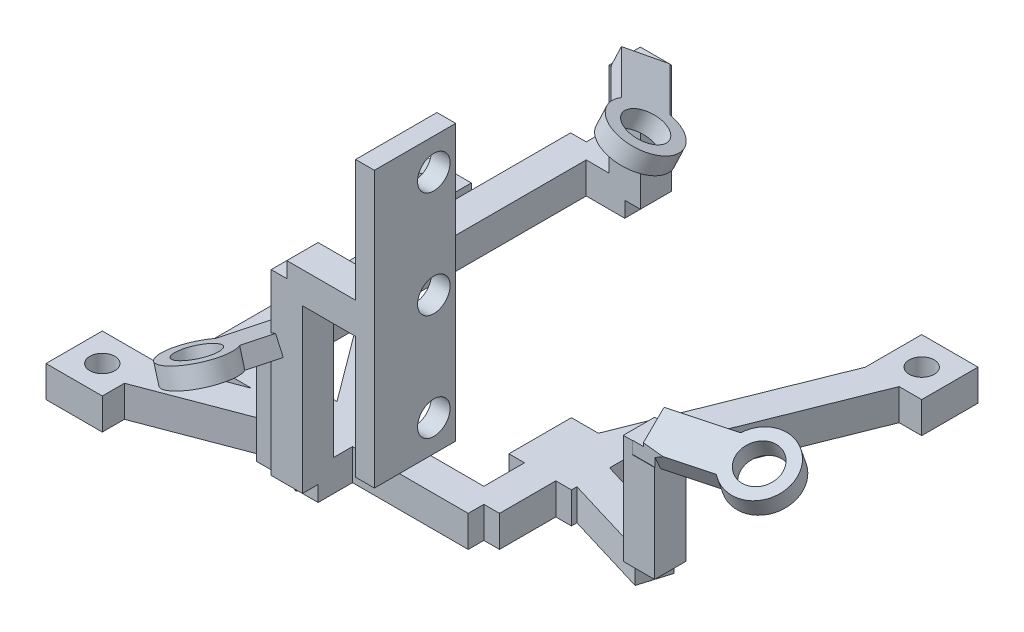
SolidWorks part; units mm, degrees
other "Cable Fairlead Support Frame"
ref_plane "Front Plane" through (0, 0, 0) normal (0, 0, 1) x (1, 0, 0)
ref_plane "Top Plane" through (0, 0, 0) normal (0, 1, 0) x (1, 0, 0)
ref_plane "Right Plane" through (0, 0, 0) normal (1, 0, 0) x (0, 0, -1)
sketch3d "Cable Fairlead Support Frame Feature profile datum points"
  point P0 (-55.2917, -60, -5)
  point P1 (-45.2917, -60, -5)
  point P2 (-55.2917, -50, -5)
ref_plane "Cable Fairlead Support Frame Feature profile plane" through (0, 0, -5) normal (0, 0, 1) x (1, 0, 0)
sketch "Cable Fairlead Support Frame Feature profile" plane through (0, 0, -5) normal (0, 0, 1) x (1, 0, 0)
  line L0 (-55.2917, -60) -> (-45.2917, -60)
  line L1 (-45.2917, -60) -> (-45.2917, -55)
  line L2 (-45.2917, -55) -> (-55.2917, -55)
  line L3 (-55.2917, -55) -> (-55.2917, -60)
extrude "Cable Fairlead Support Frame Feature" add sketch "Cable Fairlead Support Frame Feature profile" along normal blind 10 separate body
sketch3d "Frame Upper Trunk Sketch datum points"
  point P0 (-50.2917, -57.5, 0)
  point P1 (-40.2917, -57.5, 0)
  point P2 (-50.2917, -47.5, 0)
ref_plane "Frame Upper Trunk Sketch plane" through (0, 0, 0) normal (0, 0, 1) x (1, 0, 0)
sketch "Frame Upper Trunk Sketch" plane through (0, 0, 0) normal (0, 0, 1) x (1, 0, 0)
  line L0 (-52.7917, -60) -> (-47.7917, -60)
  line L1 (-47.7917, -60) -> (-47.7917, -55)
  line L2 (-47.7917, -55) -> (-52.7917, -55)
  line L3 (-52.7917, -55) -> (-52.7917, -60)
extrude "Frame Upper Trunk Feature" add sketch "Frame Upper Trunk Sketch" along normal blind 14
sketch3d "Frame Left Trunk Sketch datum points"
  point P0 (-50.2917, -57.5, 14)
  point P1 (-50.2917, -57.5, 24)
  point P2 (-50.2917, -47.5, 14)
ref_plane "Frame Left Trunk Sketch plane" through (-50.2917, 0, 0) normal (-1, 0, 0) x (0, 0, 1)
sketch "Frame Left Trunk Sketch" plane through (-50.2917, 0, 0) normal (-1, 0, 0) x (0, 0, 1)
  line L0 (11.5, -60) -> (16.5, -60)
  line L1 (16.5, -60) -> (16.5, -55)
  line L2 (16.5, -55) -> (11.5, -55)
  line L3 (11.5, -55) -> (11.5, -60)
extrude "Frame Left Trunk Feature" add sketch "Frame Left Trunk Sketch" along normal blind 21
sketch3d "Fixed Frame Mounting Web 1 Sketch datum points"
  point P0 (-71.2917, -57.5, 14)
  point P1 (-79.3163, -57.5, 19.967)
  point P2 (-71.2917, -47.5, 14)
ref_plane "Fixed Frame Mounting Web 1 Sketch plane" through (-18.6801, 0, -25.1214) normal (-0.5967, 0, -0.8025) x (-0.8025, 0, 0.5967)
sketch "Fixed Frame Mounting Web 1 Sketch" plane through (-18.6801, 0, -25.1214) normal (-0.5967, 0, -0.8025) x (-0.8025, 0, 0.5967)
  line L0 (63.0627, -60) -> (68.0627, -60)
  line L1 (68.0627, -60) -> (68.0627, -55)
  line L2 (68.0627, -55) -> (63.0627, -55)
  line L3 (63.0627, -55) -> (63.0627, -60)
extrude "Fixed Frame Mounting Web 1 Feature" add sketch "Fixed Frame Mounting Web 1 Sketch" along normal blind 48.6004
sketch3d "Prismatic M4 Mounting Pad 1 profile datum points"
  point P0 (-104.7917, -60, -29.5)
  point P1 (-94.7917, -60, -29.5)
  point P2 (-104.7917, -50, -29.5)
ref_plane "Prismatic M4 Mounting Pad 1 profile plane" through (0, 0, -29.5) normal (0, 0, 1) x (1, 0, 0)
sketch "Prismatic M4 Mounting Pad 1 profile" plane through (0, 0, -29.5) normal (0, 0, 1) x (1, 0, 0)
  line L0 (-104.7917, -60) -> (-95.7917, -60)
  line L1 (-95.7917, -60) -> (-95.7917, -55)
  line L2 (-95.7917, -55) -> (-104.7917, -55)
  line L3 (-104.7917, -55) -> (-104.7917, -60)
extrude "Prismatic M4 Mounting Pad 1" add sketch "Prismatic M4 Mounting Pad 1 profile" along normal blind 9
sketch3d "Nominal M4 Mounting Thread 1 profile datum points"
  point P0 (-100.2917, -51, -25)
  point P1 (-90.2917, -51, -25)
  point P2 (-100.2917, -51, -15)
ref_plane "Nominal M4 Mounting Thread 1 profile plane" through (0, -51, 0) normal (0, -1, 0) x (-1, 0, 0)
sketch "Nominal M4 Mounting Thread 1 profile" plane through (0, -51, 0) normal (0, -1, 0) x (-1, 0, 0)
  circle A0 centre (100.2917, 25) radius 2
extrude "Nominal M4 Mounting Thread 1" cut sketch "Nominal M4 Mounting Thread 1 profile" along normal blind 9.1
sketch3d "Fixed Frame Mounting Web 2 Sketch datum points"
  point P0 (-71.2917, -57.5, 14)
  point P1 (-67.7451, -57.5, 23.35)
  point P2 (-71.2917, -47.5, 14)
ref_plane "Fixed Frame Mounting Web 2 Sketch plane" through (-66.967, 0, 25.4013) normal (-0.935, 0, 0.3547) x (0.3547, 0, 0.935)
sketch "Fixed Frame Mounting Web 2 Sketch" plane through (-66.967, 0, 25.4013) normal (-0.935, 0, 0.3547) x (0.3547, 0, 0.935)
  line L0 (-14.6939, -60) -> (-9.6939, -60)
  line L1 (-9.6939, -60) -> (-9.6939, -55)
  line L2 (-9.6939, -55) -> (-14.6939, -55)
  line L3 (-14.6939, -55) -> (-14.6939, -60)
extrude "Fixed Frame Mounting Web 2 Feature" add sketch "Fixed Frame Mounting Web 2 Sketch" along normal blind 31.0161
sketch3d "Prismatic M4 Mounting Pad 2 profile datum points"
  point P0 (-104.7917, -60, 20.5)
  point P1 (-94.7917, -60, 20.5)
  point P2 (-104.7917, -50, 20.5)
ref_plane "Prismatic M4 Mounting Pad 2 profile plane" through (0, 0, 20.5) normal (0, 0, 1) x (1, 0, 0)
sketch "Prismatic M4 Mounting Pad 2 profile" plane through (0, 0, 20.5) normal (0, 0, 1) x (1, 0, 0)
  line L0 (-104.7917, -60) -> (-95.7917, -60)
  line L1 (-95.7917, -60) -> (-95.7917, -55)
  line L2 (-95.7917, -55) -> (-104.7917, -55)
  line L3 (-104.7917, -55) -> (-104.7917, -60)
extrude "Prismatic M4 Mounting Pad 2" add sketch "Prismatic M4 Mounting Pad 2 profile" along normal blind 9
sketch3d "Nominal M4 Mounting Thread 2 profile datum points"
  point P0 (-100.2917, -51, 25)
  point P1 (-90.2917, -51, 25)
  point P2 (-100.2917, -51, 35)
ref_plane "Nominal M4 Mounting Thread 2 profile plane" through (0, -51, 0) normal (0, -1, 0) x (-1, 0, 0)
sketch "Nominal M4 Mounting Thread 2 profile" plane through (0, -51, 0) normal (0, -1, 0) x (-1, 0, 0)
  circle A0 centre (100.2917, -25) radius 2
extrude "Nominal M4 Mounting Thread 2" cut sketch "Nominal M4 Mounting Thread 2 profile" along normal blind 9.1
sketch3d "Fixed Frame Mounting Web 3 Sketch datum points"
  point P0 (-50.2917, -57.5, 0)
  point P1 (-59.5764, -57.5, -3.7139)
  point P2 (-50.2917, -47.5, 0)
ref_plane "Fixed Frame Mounting Web 3 Sketch plane" through (-6.9368, 0, 17.3419) normal (0.3714, 0, -0.9285) x (-0.9285, 0, -0.3714)
sketch "Fixed Frame Mounting Web 3 Sketch" plane through (-6.9368, 0, 17.3419) normal (0.3714, 0, -0.9285) x (-0.9285, 0, -0.3714)
  line L0 (44.1946, -60) -> (49.1946, -60)
  line L1 (49.1946, -60) -> (49.1946, -55)
  line L2 (49.1946, -55) -> (44.1946, -55)
  line L3 (44.1946, -55) -> (44.1946, -60)
extrude "Fixed Frame Mounting Web 3 Feature" add sketch "Fixed Frame Mounting Web 3 Sketch" along normal blind 43.0813
sketch3d "Prismatic M4 Mounting Pad 3 profile datum points"
  point P0 (-38.7917, -60, -44.5)
  point P1 (-28.7917, -60, -44.5)
  point P2 (-38.7917, -50, -44.5)
ref_plane "Prismatic M4 Mounting Pad 3 profile plane" through (0, 0, -44.5) normal (0, 0, 1) x (1, 0, 0)
sketch "Prismatic M4 Mounting Pad 3 profile" plane through (0, 0, -44.5) normal (0, 0, 1) x (1, 0, 0)
  line L0 (-38.7917, -60) -> (-29.7917, -60)
  line L1 (-29.7917, -60) -> (-29.7917, -55)
  line L2 (-29.7917, -55) -> (-38.7917, -55)
  line L3 (-38.7917, -55) -> (-38.7917, -60)
extrude "Prismatic M4 Mounting Pad 3" add sketch "Prismatic M4 Mounting Pad 3 profile" along normal blind 9
sketch3d "Nominal M4 Mounting Thread 3 profile datum points"
  point P0 (-34.2917, -51, -40)
  point P1 (-24.2917, -51, -40)
  point P2 (-34.2917, -51, -30)
ref_plane "Nominal M4 Mounting Thread 3 profile plane" through (0, -51, 0) normal (0, -1, 0) x (-1, 0, 0)
sketch "Nominal M4 Mounting Thread 3 profile" plane through (0, -51, 0) normal (0, -1, 0) x (-1, 0, 0)
  circle A0 centre (34.2917, 40) radius 2
extrude "Nominal M4 Mounting Thread 3" cut sketch "Nominal M4 Mounting Thread 3 profile" along normal blind 9.1
sketch3d "Outlet Side Rise Sketch datum points"
  point P0 (-71.2917, -57.5, 14)
  point P1 (-61.2917, -57.5, 14)
  point P2 (-71.2917, -47.5, 14)
ref_plane "Outlet Side Rise Sketch plane" through (0, 0, 14) normal (0, 0, 1) x (1, 0, 0)
sketch "Outlet Side Rise Sketch" plane through (0, 0, 14) normal (0, 0, 1) x (1, 0, 0)
  line L0 (-73.7917, -60) -> (-68.7917, -60)
  line L1 (-68.7917, -60) -> (-68.7917, -55)
  line L2 (-68.7917, -55) -> (-73.7917, -55)
  line L3 (-73.7917, -55) -> (-73.7917, -60)
extrude "Outlet Side Rise Feature" add sketch "Outlet Side Rise Sketch" along normal blind 8
sketch3d "Outlet Lateral Return Sketch datum points"
  point P0 (-71.2917, -57.5, 22)
  point P1 (-61.2917, -57.5, 22)
  point P2 (-71.2917, -57.5, 12)
ref_plane "Outlet Lateral Return Sketch plane" through (0, -57.5, 0) normal (0, 1, 0) x (1, 0, 0)
sketch "Outlet Lateral Return Sketch" plane through (0, -57.5, 0) normal (0, 1, 0) x (1, 0, 0)
  line L0 (-73.7917, -24.5) -> (-68.7917, -24.5)
  line L1 (-68.7917, -24.5) -> (-68.7917, -19.5)
  line L2 (-68.7917, -19.5) -> (-73.7917, -19.5)
  line L3 (-73.7917, -19.5) -> (-73.7917, -24.5)
extrude "Outlet Lateral Return Feature" add sketch "Outlet Lateral Return Sketch" along normal blind 28.5
sketch3d "Outlet Rail Bridge Sketch datum points"
  point P0 (-71.2917, -29, 22)
  point P1 (-71.2917, -29, 12)
  point P2 (-71.2917, -19, 22)
ref_plane "Outlet Rail Bridge Sketch plane" through (-71.2917, 0, 0) normal (1, 0, 0) x (0, 0, -1)
sketch "Outlet Rail Bridge Sketch" plane through (-71.2917, 0, 0) normal (1, 0, 0) x (0, 0, -1)
  line L0 (-24.5, -31.5) -> (-19.5, -31.5)
  line L1 (-19.5, -31.5) -> (-19.5, -26.5)
  line L2 (-19.5, -26.5) -> (-24.5, -26.5)
  line L3 (-24.5, -26.5) -> (-24.5, -31.5)
extrude "Outlet Rail Bridge Feature" add sketch "Outlet Rail Bridge Sketch" along normal blind 13
sketch3d "Integral Three Lane Cable Outlet Clamp Rail profile datum points"
  point P0 (-60.2917, -51, 11.5)
  point P1 (-50.2917, -51, 11.5)
  point P2 (-60.2917, -41, 11.5)
ref_plane "Integral Three Lane Cable Outlet Clamp Rail profile plane" through (0, 0, 11.5) normal (0, 0, 1) x (1, 0, 0)
sketch "Integral Three Lane Cable Outlet Clamp Rail profile" plane through (0, 0, 11.5) normal (0, 0, 1) x (1, 0, 0)
  line L0 (-60.2917, -51) -> (-57.2917, -51)
  line L1 (-57.2917, -51) -> (-57.2917, -7)
  line L2 (-57.2917, -7) -> (-60.2917, -7)
  line L3 (-60.2917, -7) -> (-60.2917, -51)
extrude "Integral Three Lane Cable Outlet Clamp Rail" add sketch "Integral Three Lane Cable Outlet Clamp Rail profile" along normal blind 13
sketch3d "Inlet Outrigger Web 1 Sketch datum points"
  point P0 (-50.2917, -57.5, 0)
  point P1 (-47.4006, -57.5, -9.573)
  point P2 (-50.2917, -47.5, 0)
ref_plane "Inlet Outrigger Web 1 Sketch plane" through (-46.0882, 0, -13.9187) normal (0.9573, 0, 0.2891) x (0.2891, 0, -0.9573)
sketch "Inlet Outrigger Web 1 Sketch" plane through (-46.0882, 0, -13.9187) normal (0.9573, 0, 0.2891) x (0.2891, 0, -0.9573)
  line L0 (-17.0396, -60) -> (-12.0396, -60)
  line L1 (-12.0396, -60) -> (-12.0396, -55)
  line L2 (-12.0396, -55) -> (-17.0396, -55)
  line L3 (-17.0396, -55) -> (-17.0396, -60)
extrude "Inlet Outrigger Web 1 Feature" add sketch "Inlet Outrigger Web 1 Sketch" along normal blind 19.8971
sketch3d "Inlet Vertical Support 1 Sketch datum points"
  point P0 (-31.2442, -57.5, 5.7524)
  point P1 (-21.2442, -57.5, 5.7524)
  point P2 (-31.2442, -57.5, -4.2476)
ref_plane "Inlet Vertical Support 1 Sketch plane" through (0, -57.5, 0) normal (0, 1, 0) x (1, 0, 0)
sketch "Inlet Vertical Support 1 Sketch" plane through (0, -57.5, 0) normal (0, 1, 0) x (1, 0, 0)
  line L0 (-33.7442, -8.2524) -> (-28.7442, -8.2524)
  line L1 (-28.7442, -8.2524) -> (-28.7442, -3.2524)
  line L2 (-28.7442, -3.2524) -> (-33.7442, -3.2524)
  line L3 (-33.7442, -3.2524) -> (-33.7442, -8.2524)
extrude "Inlet Vertical Support 1 Feature" add sketch "Inlet Vertical Support 1 Sketch" along normal blind 17.4581
sketch3d "Inlet Collar Retaining Web 1 Sketch datum points"
  point P0 (-31.2442, -40.0419, 5.7524)
  point P1 (-32.2823, -49.2023, 1.8781)
  point P2 (-33.6151, -36.031, -3.0959)
ref_plane "Inlet Collar Retaining Web 1 Sketch plane" through (-30.5893, 0, 8.1964) normal (0.9659, 0, -0.2588) x (-0.2588, 0, -0.9659)
sketch "Inlet Collar Retaining Web 1 Sketch" plane through (-30.5893, 0, 8.1964) normal (0.9659, 0, -0.2588) x (-0.2588, 0, -0.9659)
  line L0 (-0.8175, -39.8757) -> (0.3818, -42.6147)
  line L1 (0.3818, -42.6147) -> (5.878, -40.2081)
  line L2 (5.878, -40.2081) -> (4.6787, -37.4692)
  line L3 (4.6787, -37.4692) -> (-0.8175, -39.8757)
extrude "Inlet Collar Retaining Web 1 Feature" add sketch "Inlet Collar Retaining Web 1 Sketch" along normal blind 14
sketch3d "Integral Cable Guide Clamp 1 profile datum points"
  point P0 (-17.566, -38.6724, 2.7081)
  point P1 (-7.6201, -39.6285, 2.3037)
  point P2 (-17.566, -42.5677, 11.9182)
ref_plane "Integral Cable Guide Clamp 1 profile plane" through (-3.7579, -33.1604, -14.0246) normal (-0.1038, -0.916, -0.3874) x (-0.9946, 0.0956, 0.0404)
sketch "Integral Cable Guide Clamp 1 profile" plane through (-3.7579, -33.1604, -14.0246) normal (-0.1038, -0.916, -0.3874) x (-0.9946, 0.0956, 0.0404)
  circle A0 centre (13.8831, -17.5581) radius 5
extrude "Integral Cable Guide Clamp 1" add sketch "Integral Cable Guide Clamp 1 profile" along normal blind 2.99
sketch3d "Final Cable Inlet Clamp Through Bore 1 profile datum points"
  point P0 (-17.5546, -38.5717, 2.7507)
  point P1 (-7.6086, -39.5278, 2.3463)
  point P2 (-17.5546, -42.4669, 11.9609)
ref_plane "Final Cable Inlet Clamp Through Bore 1 profile plane" through (-3.7465, -33.0597, -13.982) normal (-0.1038, -0.916, -0.3874) x (-0.9946, 0.0956, 0.0404)
sketch "Final Cable Inlet Clamp Through Bore 1 profile" plane through (-3.7465, -33.0597, -13.982) normal (-0.1038, -0.916, -0.3874) x (-0.9946, 0.0956, 0.0404)
  circle A0 centre (13.8831, -17.5581) radius 3.1
extrude "Final Cable Inlet Clamp Through Bore 1" cut sketch "Final Cable Inlet Clamp Through Bore 1 profile" along normal blind 7.2
sketch3d "Inlet Outrigger Web 2 Sketch datum points"
  point P0 (-71.2917, -57.5, 14)
  point P1 (-62.124, -57.5, 17.9944)
  point P2 (-71.2917, -47.5, 14)
ref_plane "Inlet Outrigger Web 2 Sketch plane" through (-16.5011, 0, 37.8724) normal (-0.3994, 0, 0.9168) x (0.9168, 0, 0.3994)
sketch "Inlet Outrigger Web 2 Sketch" plane through (-16.5011, 0, 37.8724) normal (-0.3994, 0, 0.9168) x (0.9168, 0, 0.3994)
  line L0 (-62.2653, -60) -> (-57.2653, -60)
  line L1 (-57.2653, -60) -> (-57.2653, -55)
  line L2 (-57.2653, -55) -> (-62.2653, -55)
  line L3 (-62.2653, -55) -> (-62.2653, -60)
extrude "Inlet Outrigger Web 2 Feature" add sketch "Inlet Outrigger Web 2 Sketch" along normal blind 7.8874
sketch3d "Inlet Vertical Support 2 Sketch datum points"
  point P0 (-74.4422, -57.5, 21.2309)
  point P1 (-64.4422, -57.5, 21.2309)
  point P2 (-74.4422, -57.5, 11.2309)
ref_plane "Inlet Vertical Support 2 Sketch plane" through (0, -57.5, 0) normal (0, 1, 0) x (1, 0, 0)
sketch "Inlet Vertical Support 2 Sketch" plane through (0, -57.5, 0) normal (0, 1, 0) x (1, 0, 0)
  line L0 (-76.9422, -23.7309) -> (-71.9422, -23.7309)
  line L1 (-71.9422, -23.7309) -> (-71.9422, -18.7309)
  line L2 (-71.9422, -18.7309) -> (-76.9422, -18.7309)
  line L3 (-76.9422, -18.7309) -> (-76.9422, -23.7309)
extrude "Inlet Vertical Support 2 Feature" add sketch "Inlet Vertical Support 2 Sketch" along normal blind 17.4535
sketch3d "Inlet Collar Retaining Web 2 Sketch datum points"
  point P0 (-74.4422, -40.0465, 21.2309)
  point P1 (-70.568, -49.2069, 22.269)
  point P2 (-65.5939, -36.0356, 23.6018)
ref_plane "Inlet Collar Retaining Web 2 Sketch plane" through (-10.2944, 0, 38.4192) normal (-0.2588, 0, 0.9659) x (0.9659, 0, 0.2588)
sketch "Inlet Collar Retaining Web 2 Sketch" plane through (-10.2944, 0, 38.4192) normal (-0.2588, 0, 0.9659) x (0.9659, 0, 0.2588)
  line L0 (-69.7564, -39.8849) -> (-68.5612, -42.6147)
  line L1 (-68.5612, -42.6147) -> (-63.0649, -40.2081)
  line L2 (-63.0649, -40.2081) -> (-64.2602, -37.4783)
  line L3 (-64.2602, -37.4783) -> (-69.7564, -39.8849)
extrude "Inlet Collar Retaining Web 2 Feature" add sketch "Inlet Collar Retaining Web 2 Sketch" along normal blind 11.5
sketch3d "Integral Cable Guide Clamp 2 profile datum points"
  point P0 (-77.9959, -38.6816, 32.1844)
  point P1 (-68.7768, -34.832, 31.7481)
  point P2 (-77.9959, -37.5556, 42.1208)
ref_plane "Integral Cable Guide Clamp 2 profile plane" through (3.3154, -7.839, 0.8884) normal (0.3874, -0.916, 0.1038) x (-0.9219, -0.385, 0.0436)
sketch "Integral Cable Guide Clamp 2 profile" plane through (3.3154, -7.839, 0.8884) normal (0.3874, -0.916, 0.1038) x (-0.9219, -0.385, 0.0436)
  circle A0 centre (88.1994, -27.624) radius 5
extrude "Integral Cable Guide Clamp 2" add sketch "Integral Cable Guide Clamp 2 profile" along normal blind 2.98
sketch3d "Final Cable Inlet Clamp Through Bore 2 profile datum points"
  point P0 (-78.0424, -38.5717, 32.1719)
  point P1 (-68.8233, -34.7221, 31.7357)
  point P2 (-78.0424, -37.4456, 42.1083)
ref_plane "Final Cable Inlet Clamp Through Bore 2 profile plane" through (3.2689, -7.7291, 0.8759) normal (0.3874, -0.916, 0.1038) x (-0.9219, -0.385, 0.0436)
sketch "Final Cable Inlet Clamp Through Bore 2 profile" plane through (3.2689, -7.7291, 0.8759) normal (0.3874, -0.916, 0.1038) x (-0.9219, -0.385, 0.0436)
  circle A0 centre (88.1994, -27.624) radius 3.1
extrude "Final Cable Inlet Clamp Through Bore 2" cut sketch "Final Cable Inlet Clamp Through Bore 2 profile" along normal blind 7.2
sketch3d "Third Inlet Cable Sweep Left Bypass Sketch datum points"
  point P0 (-71.2917, -57.5, 14)
  point P1 (-71.2917, -57.5, 24)
  point P2 (-71.2917, -47.5, 14)
ref_plane "Third Inlet Cable Sweep Left Bypass Sketch plane" through (-71.2917, 0, 0) normal (-1, 0, 0) x (0, 0, 1)
sketch "Third Inlet Cable Sweep Left Bypass Sketch" plane through (-71.2917, 0, 0) normal (-1, 0, 0) x (0, 0, 1)
  line L0 (11.5, -60) -> (16.5, -60)
  line L1 (16.5, -60) -> (16.5, -55)
  line L2 (16.5, -55) -> (11.5, -55)
  line L3 (11.5, -55) -> (11.5, -60)
extrude "Third Inlet Cable Sweep Left Bypass Feature" add sketch "Third Inlet Cable Sweep Left Bypass Sketch" along normal blind 21
sketch3d "Third Inlet Cable Sweep Lower Bypass Sketch datum points"
  point P0 (-92.2917, -57.5, 14)
  point P1 (-102.2917, -57.5, 14)
  point P2 (-92.2917, -47.5, 14)
ref_plane "Third Inlet Cable Sweep Lower Bypass Sketch plane" through (0, 0, 14) normal (0, 0, -1) x (-1, 0, 0)
sketch "Third Inlet Cable Sweep Lower Bypass Sketch" plane through (0, 0, 14) normal (0, 0, -1) x (-1, 0, 0)
  line L0 (89.7917, -60) -> (94.7917, -60)
  line L1 (94.7917, -60) -> (94.7917, -55)
  line L2 (94.7917, -55) -> (89.7917, -55)
  line L3 (89.7917, -55) -> (89.7917, -60)
extrude "Third Inlet Cable Sweep Lower Bypass Feature" add sketch "Third Inlet Cable Sweep Lower Bypass Sketch" along normal blind 58.3669
sketch3d "Third Inlet Cable Sweep Return Sketch datum points"
  point P0 (-92.2917, -57.5, -44.3669)
  point P1 (-92.2917, -57.5, -54.3669)
  point P2 (-92.2917, -47.5, -44.3669)
ref_plane "Third Inlet Cable Sweep Return Sketch plane" through (-92.2917, 0, 0) normal (1, 0, 0) x (0, 0, -1)
sketch "Third Inlet Cable Sweep Return Sketch" plane through (-92.2917, 0, 0) normal (1, 0, 0) x (0, 0, -1)
  line L0 (41.8669, -60) -> (46.8669, -60)
  line L1 (46.8669, -60) -> (46.8669, -55)
  line L2 (46.8669, -55) -> (41.8669, -55)
  line L3 (41.8669, -55) -> (41.8669, -60)
extrude "Third Inlet Cable Sweep Return Feature" add sketch "Third Inlet Cable Sweep Return Sketch" along normal blind 8.659
sketch3d "Inlet Vertical Support 3 Sketch datum points"
  point P0 (-83.6327, -57.5, -44.3669)
  point P1 (-73.6327, -57.5, -44.3669)
  point P2 (-83.6327, -57.5, -54.3669)
ref_plane "Inlet Vertical Support 3 Sketch plane" through (0, -57.5, 0) normal (0, 1, 0) x (1, 0, 0)
sketch "Inlet Vertical Support 3 Sketch" plane through (0, -57.5, 0) normal (0, 1, 0) x (1, 0, 0)
  line L0 (-86.1327, 41.8669) -> (-81.1327, 41.8669)
  line L1 (-81.1327, 41.8669) -> (-81.1327, 46.8669)
  line L2 (-81.1327, 46.8669) -> (-86.1327, 46.8669)
  line L3 (-86.1327, 46.8669) -> (-86.1327, 41.8669)
extrude "Inlet Vertical Support 3 Feature" add sketch "Inlet Vertical Support 3 Sketch" along normal blind 17.4581
sketch3d "Inlet Collar Retaining Web 3 Sketch datum points"
  point P0 (-83.6327, -40.0419, -44.3669)
  point P1 (-86.4688, -49.2023, -41.5308)
  point P2 (-77.1553, -44.0528, -50.8443)
ref_plane "Inlet Collar Retaining Web 3 Sketch plane" through (-63.9998, 0, -63.9998) normal (0.7071, 0, 0.7071) x (0.7071, 0, -0.7071)
sketch "Inlet Collar Retaining Web 3 Sketch" plane through (-63.9998, 0, -63.9998) normal (0.7071, 0, 0.7071) x (0.7071, 0, -0.7071)
  line L0 (-29.9136, -37.4692) -> (-31.1128, -40.2081)
  line L1 (-31.1128, -40.2081) -> (-25.6166, -42.6147)
  line L2 (-25.6166, -42.6147) -> (-24.4174, -39.8757)
  line L3 (-24.4174, -39.8757) -> (-29.9136, -37.4692)
extrude "Inlet Collar Retaining Web 3 Feature" add sketch "Inlet Collar Retaining Web 3 Sketch" along normal blind 14
sketch3d "Integral Cable Guide Clamp 3 profile datum points"
  point P0 (-73.3092, -38.6724, -34.8914)
  point P1 (-63.7198, -41.3817, -34.0526)
  point P2 (-73.3092, -35.7149, -25.3388)
ref_plane "Integral Cable Guide Clamp 3 profile plane" through (-13.1373, -42.4321, 13.1373) normal (-0.2836, -0.916, 0.2836) x (-0.9589, 0.2709, -0.0839)
sketch "Integral Cable Guide Clamp 3 profile" plane through (-13.1373, -42.4321, 13.1373) normal (-0.2836, -0.916, 0.2836) x (-0.9589, 0.2709, -0.0839)
  circle A0 centre (62.7484, 44.7681) radius 5
extrude "Integral Cable Guide Clamp 3" add sketch "Integral Cable Guide Clamp 3 profile" along normal blind 2.99
sketch3d "Final Cable Inlet Clamp Through Bore 3 profile datum points"
  point P0 (-73.278, -38.5717, -34.9226)
  point P1 (-63.6886, -41.2809, -34.0838)
  point P2 (-73.278, -35.6141, -25.37)
ref_plane "Final Cable Inlet Clamp Through Bore 3 profile plane" through (-13.1061, -42.3313, 13.1061) normal (-0.2836, -0.916, 0.2836) x (-0.9589, 0.2709, -0.0839)
sketch "Final Cable Inlet Clamp Through Bore 3 profile" plane through (-13.1061, -42.3313, 13.1061) normal (-0.2836, -0.916, 0.2836) x (-0.9589, 0.2709, -0.0839)
  circle A0 centre (62.7484, 44.7681) radius 3.1
extrude "Final Cable Inlet Clamp Through Bore 3" cut sketch "Final Cable Inlet Clamp Through Bore 3 profile" along normal blind 7.2
sketch3d "Cable Outlet Clamp Bore 1 profile datum points"
  point P0 (-62.3917, -12, 15)
  point P1 (-62.3917, -2, 15)
  point P2 (-62.3917, -12, 25)
ref_plane "Cable Outlet Clamp Bore 1 profile plane" through (-62.3917, 0, 0) normal (1, 0, 0) x (0, 0, -1)
sketch "Cable Outlet Clamp Bore 1 profile" plane through (-62.3917, 0, 0) normal (1, 0, 0) x (0, 0, -1)
  circle A0 centre (-15, -12) radius 2.6
extrude "Cable Outlet Clamp Bore 1" cut sketch "Cable Outlet Clamp Bore 1 profile" along normal blind 7.4
sketch3d "Cable Outlet Clamp Bore 2 profile datum points"
  point P0 (-62.3917, -29, 15)
  point P1 (-62.3917, -19, 15)
  point P2 (-62.3917, -29, 25)
ref_plane "Cable Outlet Clamp Bore 2 profile plane" through (-62.3917, 0, 0) normal (1, 0, 0) x (0, 0, -1)
sketch "Cable Outlet Clamp Bore 2 profile" plane through (-62.3917, 0, 0) normal (1, 0, 0) x (0, 0, -1)
  circle A0 centre (-15, -29) radius 2.6
extrude "Cable Outlet Clamp Bore 2" cut sketch "Cable Outlet Clamp Bore 2 profile" along normal blind 7.4
sketch3d "Outlet Rear Nut Seating Clearance 2 profile datum points"
  point P0 (-62.3917, -29, 15)
  point P1 (-62.3917, -19, 15)
  point P2 (-62.3917, -29, 25)
ref_plane "Outlet Rear Nut Seating Clearance 2 profile plane" through (-62.3917, 0, 0) normal (1, 0, 0) x (0, 0, -1)
sketch "Outlet Rear Nut Seating Clearance 2 profile" plane through (-62.3917, 0, 0) normal (1, 0, 0) x (0, 0, -1)
  circle A0 centre (-15, -29) radius 4.75
extrude "Outlet Rear Nut Seating Clearance 2" cut sketch "Outlet Rear Nut Seating Clearance 2 profile" along normal blind 2.1
sketch3d "Cable Outlet Clamp Bore 3 profile datum points"
  point P0 (-62.3917, -46, 15)
  point P1 (-62.3917, -36, 15)
  point P2 (-62.3917, -46, 25)
ref_plane "Cable Outlet Clamp Bore 3 profile plane" through (-62.3917, 0, 0) normal (1, 0, 0) x (0, 0, -1)
sketch "Cable Outlet Clamp Bore 3 profile" plane through (-62.3917, 0, 0) normal (1, 0, 0) x (0, 0, -1)
  circle A0 centre (-15, -46) radius 2.6
extrude "Cable Outlet Clamp Bore 3" cut sketch "Cable Outlet Clamp Bore 3 profile" along normal blind 7.4
sketch3d "First Inlet Web Comb Corner Clearance profile datum points"
  point P0 (-32.2917, -42, 8.2)
  point P1 (-22.2917, -42, 8.2)
  point P2 (-32.2917, -32, 8.2)
ref_plane "First Inlet Web Comb Corner Clearance profile plane" through (0, 0, 8.2) normal (0, 0, 1) x (1, 0, 0)
sketch "First Inlet Web Comb Corner Clearance profile" plane through (0, 0, 8.2) normal (0, 0, 1) x (1, 0, 0)
  line L0 (-32.2917, -42) -> (-27.2917, -42)
  line L1 (-27.2917, -42) -> (-27.2917, -38)
  line L2 (-27.2917, -38) -> (-32.2917, -38)
  line L3 (-32.2917, -38) -> (-32.2917, -42)
extrude "First Inlet Web Comb Corner Clearance" cut sketch "First Inlet Web Comb Corner Clearance profile" along normal blind 1.3
sketch3d "First Wall Mount Outer Corner Rail Head Clearance profile datum points"
  point P0 (-104.8917, -56.2, -29.6)
  point P1 (-94.8917, -56.2, -29.6)
  point P2 (-104.8917, -46.2, -29.6)
ref_plane "First Wall Mount Outer Corner Rail Head Clearance profile plane" through (0, 0, -29.6) normal (0, 0, 1) x (1, 0, 0)
sketch "First Wall Mount Outer Corner Rail Head Clearance profile" plane through (0, 0, -29.6) normal (0, 0, 1) x (1, 0, 0)
  line L0 (-104.8917, -56.2) -> (-103.0917, -56.2)
  line L1 (-103.0917, -56.2) -> (-103.0917, -54.9)
  line L2 (-103.0917, -54.9) -> (-104.8917, -54.9)
  line L3 (-104.8917, -54.9) -> (-104.8917, -56.2)
extrude "First Wall Mount Outer Corner Rail Head Clearance" cut sketch "First Wall Mount Outer Corner Rail Head Clearance profile" along normal blind 5.1
